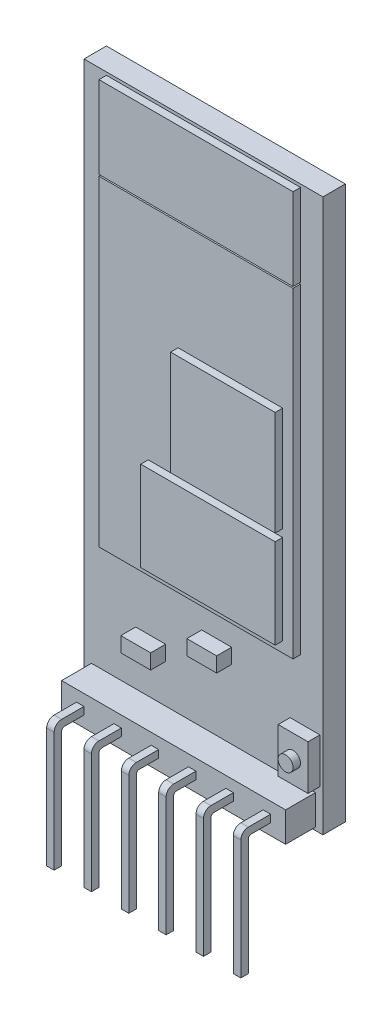
SolidWorks part; units mm, degrees
ref_plane "Front" through (0, 0, 0) normal (0, 0, 1) x (1, 0, 0)
ref_plane "Top" through (0, 0, 0) normal (0, 1, 0) x (1, 0, 0)
ref_plane "Right" through (0, 0, 0) normal (1, 0, 0) x (0, 0, -1)
sketch "草图1" plane through (0, 0, 0) normal (0, 0, 1) x (1, 0, 0)
  line L1 (0, 0) -> (16, 0)
  line L2 (0, 0) -> (0, 37)
  line L3 (0, 37) -> (16, 37)
  line L4 (16, 0) -> (16, 37)
  dimension "D1" = 37
  dimension "D2" = 16
extrude "凸台-拉伸1" add sketch "草图1" along normal blind 1.5
sketch "草图2" plane through (0, 0, 1.5) normal (0, 0, 1) x (1, 0, 0)
  line L1 (0.5, 2.2) -> (15.5, 2.2)
  line L2 (0.5, 2.2) -> (0.5, 0.2)
  line L3 (0.5, 0.2) -> (15.5, 0.2)
  line L4 (15.5, 2.2) -> (15.5, 0.2)
  line L5 (0, 37) -> (0, 0) construction
  line L6 (0, 0) -> (16, 0) construction
  dimension "D1" = 15
  dimension "D2" = 2
  dimension "D3" = 0.5
  dimension "D4" = 0.2
extrude "凸台-拉伸2" add sketch "草图2" along normal blind 2
sketch "草图3" plane through (0, 0, 3.5) normal (0, 0, 1) x (1, 0, 0)
  line L0 (15.5, 2.2) -> (0.5, 2.2) construction
  line L1 (1.5, 1.45) -> (2, 1.45)
  line L2 (1.5, 1.45) -> (1.5, 0.95)
  line L3 (1.5, 0.95) -> (2, 0.95)
  line L4 (2, 1.45) -> (2, 0.95)
  line L5 (0.5, 2.2) -> (0.5, 0.2) construction
  dimension "D1" = 0.5
  dimension "D2" = 0.5
  dimension "D3" = 0.75
  dimension "D4" = 1
extrude "凸台-拉伸3" add sketch "草图3" along normal blind 2
sketch "草图4" plane through (0, 0.95, 0) normal (0, -1, 0) x (1, 0, 0)
  line L0 (2, 5.5) -> (2, 3.5) construction
  line L1 (1.5, 5.5) -> (2, 5.5)
  line L2 (1.5, 5.5) -> (1.5, 5)
  line L3 (1.5, 5) -> (2, 5)
  line L4 (2, 5.5) -> (2, 5)
  dimension "D1" = 0.5
extrude "凸台-拉伸4" add sketch "草图4" along normal blind 8
sketch "草图5" plane through (0, -7.05, 0) normal (0, -1, 0) x (1, 0, 0)
  line L0 (1.5, 5) -> (1.5, 3.5) construction
  line L1 (0.5, 4) -> (3, 4)
  line L2 (0.5, 4) -> (0.5, 6.5)
  line L3 (0.5, 6.5) -> (3, 6.5)
  line L4 (3, 4) -> (3, 6.5)
  line L5 (0.5, 4) -> (3, 6.5) construction
  line L6 (0.5, 6.5) -> (3, 4) construction
  line L7 (2, 5.5) -> (1.5, 5.5) construction
  point P0 (1.75, 5.25)
  dimension "D1" = 2.5
  dimension "D2" = 2.5
  dimension "D3" = 1
  dimension "D4" = 1
fillet "圆角2" radius 0.5 1 edges at (1.75, 1.45, 5.5)
fillet "圆角3" radius 0.2 1 edges at (1.75, 0.95, 5)
pattern_linear "阵列(线性)1" count 6 spacing 2.5 along (1, 0, 0) of "圆角2", "凸台-拉伸3", "凸台-拉伸4", "圆角3"
sketch "草图7" plane through (0, 0, 1.5) normal (0, 0, 1) x (1, 0, 0)
  line L0 (16, 37) -> (0, 37) construction
  line L1 (14.5, 36.8) -> (1.5, 36.8)
  line L2 (14.5, 36.8) -> (14.5, 31.3)
  line L3 (14.5, 31.3) -> (1.5, 31.3)
  line L4 (1.5, 36.8) -> (1.5, 31.3)
  line L5 (16, 0) -> (16, 37) construction
  dimension "D1" = 5.5
  dimension "D2" = 13
  dimension "D3" = 0.2
  dimension "D4" = 1.5
extrude "凸台-拉伸7" add sketch "草图7" along normal blind 0.5
sketch "草图8" plane through (0, 0, 1.5) normal (0, 0, 1) x (1, 0, 0)
  line L0 (16, 37) -> (0, 37) construction
  line L1 (1.5, 31.2) -> (14.5, 31.2)
  line L2 (1.5, 31.2) -> (1.5, 9.7)
  line L3 (1.5, 9.7) -> (14.5, 9.7)
  line L4 (14.5, 31.2) -> (14.5, 9.7)
  dimension "D1" = 21.5
  dimension "D2" = 5.8
extrude "凸台-拉伸8" add sketch "草图8" along normal blind 0.5
sketch "草图9" plane through (0, 0, 1.5) normal (0, 0, 1) x (1, 0, 0)
  line L0 (16, 0) -> (16, 37) construction
  line L1 (15.8, 5.7) -> (13.8, 5.7)
  line L2 (15.8, 5.7) -> (15.8, 2.7)
  line L3 (15.8, 2.7) -> (13.8, 2.7)
  line L4 (13.8, 5.7) -> (13.8, 2.7)
  line L5 (15.5, 2.2) -> (0.5, 2.2) construction
  dimension "D1" = 3
  dimension "D2" = 2
  dimension "D3" = 0.2
  dimension "D4" = 0.5
extrude "凸台-拉伸9" add sketch "草图9" along normal blind 0.8
sketch "草图10" plane through (0, 0, 2.3) normal (0, 0, 1) x (1, 0, 0)
  line L0 (15.8, 2.7) -> (15.8, 5.7) construction
  line L1 (15.8, 5.7) -> (13.8, 5.7) construction
  circle A0 centre (14.8, 4.2) radius 0.5
  point P4 (15.8, 4.2)
  point P7 (14.8, 5.7)
  dimension "D1" = 0
  dimension "D2" = 0
extrude "凸台-拉伸10" add sketch "草图10" along normal blind 0.5
sketch "草图11" plane through (0, 0, 1.5) normal (0, 0, 1) x (1, 0, 0)
  line L1 (9.8826, 7.825) -> (7.8826, 7.825)
  line L2 (9.8826, 7.825) -> (9.8826, 6.825)
  line L3 (9.8826, 6.825) -> (7.8826, 6.825)
  line L4 (7.8826, 7.825) -> (7.8826, 6.825)
  line L5 (5.4642, 5.7887) -> (3.4642, 5.7887)
  line L6 (5.4642, 5.7887) -> (5.4642, 4.7887)
  line L7 (5.4642, 4.7887) -> (3.4642, 4.7887)
  line L8 (3.4642, 5.7887) -> (3.4642, 4.7887)
  dimension "D1" = 1
  dimension "D2" = 2
  dimension "D3" = 1
  dimension "D4" = 2
extrude "凸台-拉伸11" add sketch "草图11" along normal blind 1
sketch "草图12" plane through (0, 0, 2) normal (0, 0, 1) x (1, 0, 0)
  line L0 (14.5, 9.7) -> (14.5, 31.2) construction
  line L1 (13.8, 23.9) -> (6.8, 23.9)
  line L2 (13.8, 23.9) -> (13.8, 16.9)
  line L3 (13.8, 16.9) -> (6.8, 16.9)
  line L4 (6.8, 23.9) -> (6.8, 16.9)
  line L5 (13.8, 16.4) -> (4.8, 16.4)
  line L6 (13.8, 16.4) -> (13.8, 10.4)
  line L7 (13.8, 10.4) -> (4.8, 10.4)
  line L8 (4.8, 16.4) -> (4.8, 10.4)
  line L9 (1.5, 9.7) -> (14.5, 9.7) construction
  dimension "D1" = 7
  dimension "D2" = 7
  dimension "D3" = 6
  dimension "D4" = 9
  dimension "D5" = 0.7
  dimension "D6" = 0.7
  dimension "D7" = 0.5
  dimension "D8" = 0.7
extrude "凸台-拉伸12" add sketch "草图12" along normal blind 0.5
